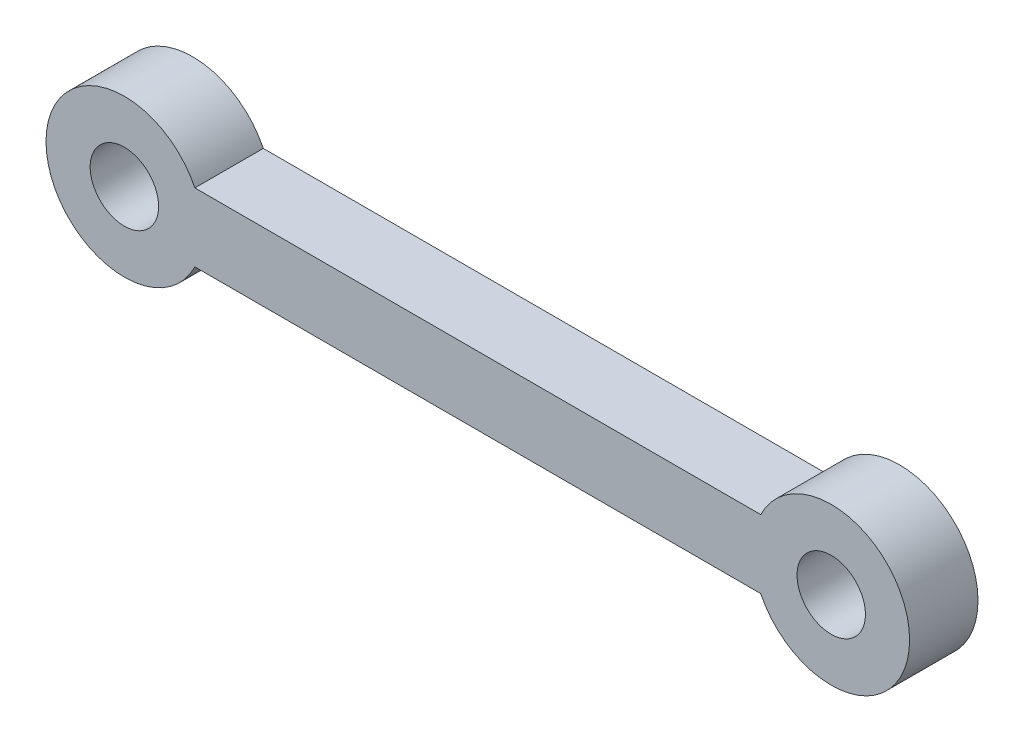
SolidWorks part; units mm, degrees
ref_plane "Front Plane" through (0, 0, 0) normal (0, 0, 1) x (1, 0, 0)
ref_plane "Top Plane" through (0, 0, 0) normal (0, 1, 0) x (1, 0, 0)
ref_plane "Right Plane" through (0, 0, 0) normal (1, 0, 0) x (0, 0, -1)
sketch "Sketch2" plane through (0, 0, 0) normal (0, 0, 1) x (1, 0, 0)
  line L0 (-14.1058, 0) -> (16.8942, 0) construction
  line L1 (-14.1058, 3.5) -> (16.8942, 3.5) construction
  line L2 (-14.1058, -3.5) -> (16.8942, -3.5) construction
  line L3 (1.3942, 0) -> (1.3942, -3.5) construction
  line L5 (-11.0139, 1.5) -> (13.8022, 1.5)
  line L7 (-11.0139, -1.5) -> (13.8022, -1.5)
  line L9 (-11.0139, 1.5) -> (13.8022, -1.5) construction
  line L10 (-11.0139, -1.5) -> (13.8022, 1.5) construction
  arc A0 (-14.1058, 3.5) -> (-14.1058, -3.5) centre (-14.1058, 0) ccw construction
  arc A1 (16.8942, -3.5) -> (16.8942, 3.5) centre (16.8942, 0) ccw construction
  circle A2 centre (-14.1058, 0) radius 1.5
  circle A3 centre (-14.1058, 0) radius 3.4366
  circle A4 centre (16.8942, 0) radius 3.4366
  circle A5 centre (16.8942, 0) radius 1.5
  point P3 (1.3942, 0)
  dimension "D3" = 3
  dimension "D1" = 31
  dimension "D2" = 7
  dimension "D4" = 3
extrude "Boss-Extrude1" add sketch "Sketch2" along normal blind 3 contours A3 A2 | L7 A4 L5 A3 | A4 A5
